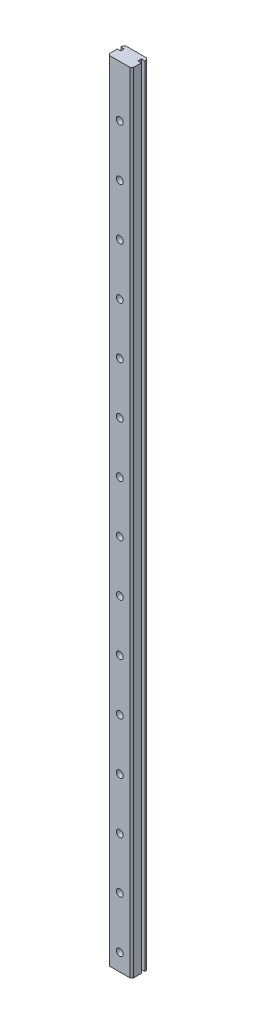
SolidWorks part; units mm, degrees
material "AISI 304"
ref_plane "前视基准面" through (0, 0, 0) normal (0, 0, 1) x (1, 0, 0)
ref_plane "上视基准面" through (0, 0, 0) normal (0, 1, 0) x (1, 0, 0)
ref_plane "右视基准面" through (0, 0, 0) normal (1, 0, 0) x (0, 0, -1)
other "Configuration Table"
sketch "草图1" plane through (0, 0, 0) normal (0, 1, 0) x (1, 0, 0)
  line L0 (0, 0) -> (0, 7.157) construction
  line L1 (-3.5, -2.4) -> (3.5, -2.4)
  line L2 (-3.5, -2.4) -> (-3.5, 2.4)
  line L3 (-3.5, 2.4) -> (3.5, 2.4)
  line L4 (3.5, -2.4) -> (3.5, 2.4)
  line L5 (-3.5, -2.4) -> (3.5, 2.4) construction
  line L6 (-3.5, 2.4) -> (3.5, -2.4) construction
  line L7 (3.5, 1.4) -> (2.5, 1.4)
  line L8 (2.5, 1.4) -> (2.5, 0.4)
  line L9 (2.5, 0.4) -> (3.5, 0.4)
  line L10 (-2.5, 0.4) -> (-3.5, 0.4)
  line L11 (-2.5, 1.4) -> (-2.5, 0.4)
  line L12 (-3.5, 1.4) -> (-2.5, 1.4)
  point P0 (0, 0)
  dimension "D1" = 7
  dimension "D2" = 4.8
  dimension "D3" = 1
  dimension "D4" = 1
  dimension "D5" = 1
extrude "凸台-拉伸1" add sketch "草图1" along normal blind 230 contours L2 L12 L11 L10 L1 L4 L9 L8 L7 L3
sketch "草图2" plane through (0, 0, -2.4) normal (0, 0, -1) x (-1, 0, 0)
  line L0 (3.5, 0) -> (-3.5, 0) construction
  line L1 (-3.5, 230) -> (-3.5, 0) construction
  circle A0 centre (0, 5) radius 1
  circle A1 centre (0, 20) radius 1
  circle A2 centre (0, 35) radius 1
  circle A3 centre (0, 50) radius 1
  circle A4 centre (0, 65) radius 1
  circle A5 centre (0, 80) radius 1
  circle A6 centre (0, 95) radius 1
  circle A7 centre (0, 110) radius 1
  circle A8 centre (0, 125) radius 1
  circle A9 centre (0, 140) radius 1
  circle A10 centre (0, 155) radius 1
  circle A11 centre (0, 170) radius 1
  circle A12 centre (0, 185) radius 1
  circle A13 centre (0, 200) radius 1
  circle A14 centre (0, 215) radius 1
  dimension "D1" = 2
  dimension "D2" = 5
  dimension "D5" = 15
  dimension "D3" = 3.5
  dimension "D4" = 15
extrude "切除-拉伸1" cut sketch "草图2" against normal blind 10
chamfer "倒角1" distance 0.5 angle 45 4 edges at (-3.5, 115, 2.4) (3.5, 115, 2.4) (-3.5, 115, -2.4) (3.5, 115, -2.4)
sketch "草图3" plane through (0, 0, -2.4) normal (0, 0, -1) x (-1, 0, 0)
  circle A0 centre (0, 5) radius 2.3833
  circle A1 centre (0, 20) radius 2.3833
  circle A2 centre (0, 35) radius 2.3833
  circle A3 centre (0, 50) radius 2.3833
  circle A4 centre (0, 65) radius 2.3833
  circle A5 centre (0, 80) radius 2.3833
  circle A6 centre (0, 95) radius 2.3833
  circle A7 centre (0, 110) radius 2.3833
  circle A8 centre (0, 125) radius 2.3833
  circle A9 centre (0, 140) radius 2.3833
  circle A10 centre (0, 155) radius 2.3833
  circle A11 centre (0, 170) radius 2.3833
  circle A12 centre (0, 185) radius 2.3833
  circle A13 centre (0, 200) radius 2.3833
  circle A14 centre (0, 215) radius 2.3833
  dimension "D1" = 4.7666
  dimension "D3" = 15
  dimension "D2" = 15
extrude "切除-拉伸2" cut sketch "草图3" against normal blind 1
